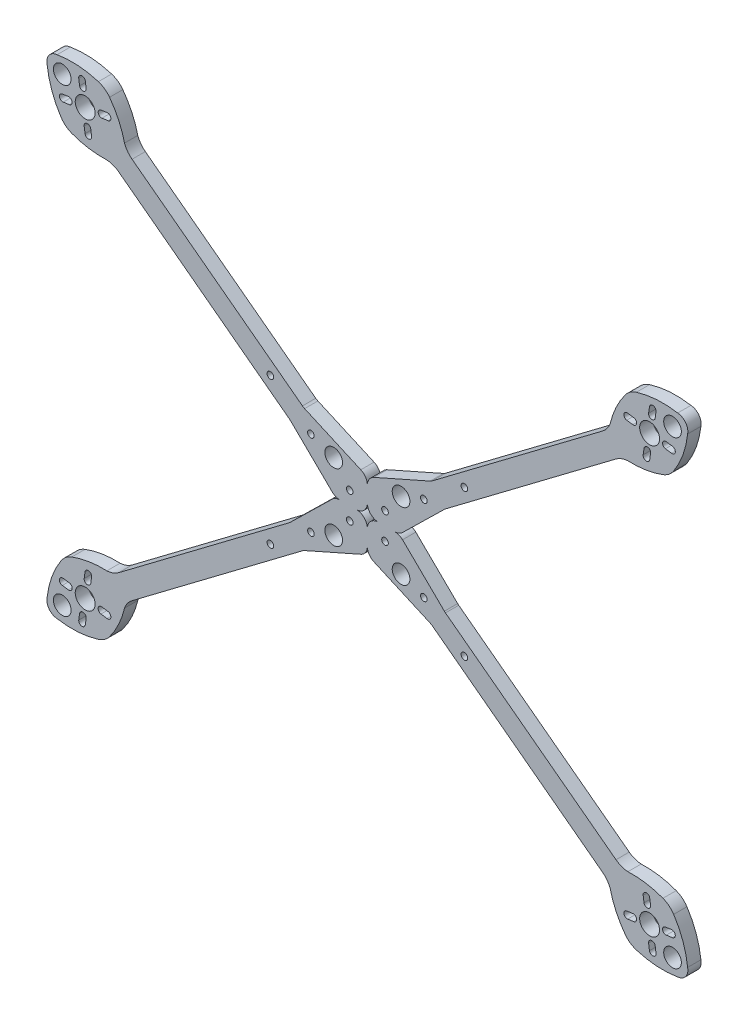
SolidWorks part; units mm, degrees
ref_plane "Alzado" through (0, 0, 0) normal (0, 0, 1) x (1, 0, 0)
ref_plane "Planta" through (0, 0, 0) normal (0, 1, 0) x (1, 0, 0)
ref_plane "Vista lateral" through (0, 0, 0) normal (1, 0, 0) x (0, 0, -1)
sketch "Croquis1" plane through (0, 0, 0) normal (0, 0, 1) x (1, 0, 0)
  line L0 (-166.1256, 84.824) -> (-181.6394, 96.5144) construction
  line L1 (-181.6394, 96.5144) -> (-187.6575, 88.5281) construction
  line L2 (-187.6575, 88.5281) -> (-171.8329, 76.6034) construction
  line L3 (-136.7303, 61.4124) -> (-136.7303, 68.4084)
  line L4 (-139.7056, 72.9801) -> (-165.1413, 84.2454)
  line L5 (-136.7303, 56.4124) -> (-264.512, 152.7028) construction
  line L6 (-141.7303, 56.4124) -> (-149.1592, 56.4124)
  line L7 (-152.6561, 57.8386) -> (-171.6025, 76.3779)
  line L8 (-264.512, 152.7028) -> (-274.8943, 160.5264) construction
  line L9 (-264.512, 152.7028) -> (-266.1473, 164.3384) construction
  line L11 (-267.4239, 162.6443) -> (-267.0343, 159.8715)
  line L15 (-264.0635, 160.289) -> (-264.4531, 163.0618)
  line L19 (-267.6327, 164.1297) -> (-267.4239, 162.6443) construction
  line L20 (-267.4239, 162.6443) -> (-264.4531, 163.0618) construction
  line L21 (-266.8255, 158.3861) -> (-267.0343, 159.8715) construction
  line L22 (-267.0343, 159.8715) -> (-264.0635, 160.289) construction
  line L23 (-254.5705, 155.6147) -> (-257.3433, 155.225)
  line L24 (-256.9258, 152.2542) -> (-254.153, 152.6439)
  line L25 (-261.6001, 142.7613) -> (-261.9898, 145.534)
  line L26 (-264.9606, 145.1165) -> (-264.5709, 142.3438)
  line L27 (-274.4535, 149.7908) -> (-271.6808, 150.1805)
  line L28 (-272.0983, 153.1513) -> (-274.871, 152.7616)
  line L29 (-172.0904, 76.7974) -> (-249.3006, 134.9795)
  line L30 (-264.512, 152.7028) -> (-273.5392, 140.7232) construction
  line L31 (-263.0855, 142.5525) -> (-262.8767, 141.0671) construction
  line L32 (-274.8943, 160.5264) -> (-282.8806, 166.5445) construction
  line L33 (-262.8767, 141.0671) -> (-262.3693, 137.4568) construction
  line L34 (-274.6623, 151.2762) -> (-276.1477, 151.0675) construction
  line L35 (-276.1477, 151.0675) -> (-279.6136, 150.5804) construction
  line L36 (-165.8148, 84.5898) -> (-243.2825, 142.9659)
  line L37 (-276.1477, -38.2428) -> (-279.6136, -37.7557) construction
  line L38 (-274.6623, -38.4515) -> (-276.1477, -38.2428) construction
  line L39 (-262.8767, -28.2424) -> (-262.3693, -24.6321) construction
  line L40 (-274.8943, -47.7016) -> (-282.8806, -53.7198) construction
  line L41 (-263.0855, -29.7278) -> (-262.8767, -28.2424) construction
  line L42 (-264.512, -39.878) -> (-273.5392, -27.8985) construction
  line L43 (-267.0343, -47.0468) -> (-264.0635, -47.4643) construction
  line L44 (-266.8255, -45.5614) -> (-267.0343, -47.0468) construction
  line L45 (-267.4239, -49.8195) -> (-264.4531, -50.237) construction
  line L46 (-267.6327, -51.3049) -> (-267.4239, -49.8195) construction
  line L47 (-264.512, -39.878) -> (-266.1473, -51.5137) construction
  line L48 (-264.512, -39.878) -> (-274.8943, -47.7016) construction
  line L49 (-136.7303, 56.4124) -> (-264.512, -39.878) construction
  line L50 (-187.6575, 24.2966) -> (-171.8329, 36.2213) construction
  line L51 (-181.6394, 16.3103) -> (-187.6575, 24.2966) construction
  line L52 (-166.1256, 28.0008) -> (-181.6394, 16.3103) construction
  line L53 (-165.8148, 28.235) -> (-243.2825, -30.1411)
  line L54 (-172.0904, 36.0273) -> (-249.3006, -22.1548)
  line L55 (-272.0983, -40.3266) -> (-274.871, -39.9369)
  line L56 (-274.4535, -36.9661) -> (-271.6808, -37.3558)
  line L57 (-264.9606, -32.2918) -> (-264.5709, -29.519)
  line L58 (-261.6001, -29.9366) -> (-261.9898, -32.7093)
  line L59 (-256.9258, -39.4295) -> (-254.153, -39.8192)
  line L60 (-254.5705, -42.79) -> (-257.3433, -42.4003)
  line L61 (-264.0635, -47.4643) -> (-264.4531, -50.237)
  line L62 (-267.4239, -49.8195) -> (-267.0343, -47.0468)
  line L63 (-152.6561, 54.9861) -> (-171.6025, 36.4468)
  line L64 (-139.7056, 39.8447) -> (-165.1413, 28.5793)
  line L65 (-136.7303, 51.4124) -> (-136.7303, 44.4163)
  line L66 (-107.3351, 28.0008) -> (-91.8213, 16.3103) construction
  line L67 (-91.8213, 16.3103) -> (-85.8031, 24.2966) construction
  line L68 (-85.8031, 24.2966) -> (-101.6277, 36.2213) construction
  line L69 (-136.7303, 56.4124) -> (-8.9487, -39.878) construction
  line L70 (-8.9487, -39.878) -> (1.4336, -47.7016) construction
  line L71 (-8.9487, -39.878) -> (-7.3134, -51.5137) construction
  line L72 (-5.828, -51.3049) -> (-6.0367, -49.8195) construction
  line L73 (-6.0367, -49.8195) -> (-9.0075, -50.237) construction
  line L74 (-6.6352, -45.5614) -> (-6.4264, -47.0468) construction
  line L75 (-6.4264, -47.0468) -> (-9.3972, -47.4643) construction
  line L76 (-8.9487, -39.878) -> (0.0786, -27.8985) construction
  line L77 (-10.3752, -29.7278) -> (-10.5839, -28.2424) construction
  line L78 (1.4336, -47.7016) -> (9.42, -53.7198) construction
  line L79 (-10.5839, -28.2424) -> (-11.0913, -24.6321) construction
  line L80 (1.2016, -38.4515) -> (2.687, -38.2428) construction
  line L81 (2.687, -38.2428) -> (6.1529, -37.7557) construction
  line L82 (2.687, 151.0675) -> (6.1529, 150.5804) construction
  line L83 (1.2016, 151.2762) -> (2.687, 151.0675) construction
  line L84 (-10.5839, 141.0671) -> (-11.0913, 137.4568) construction
  line L85 (1.4336, 160.5264) -> (9.42, 166.5445) construction
  line L86 (-10.3752, 142.5525) -> (-10.5839, 141.0671) construction
  line L87 (-8.9487, 152.7028) -> (0.0786, 140.7232) construction
  line L88 (-6.4264, 159.8715) -> (-9.3972, 160.289) construction
  line L89 (-6.6352, 158.3861) -> (-6.4264, 159.8715) construction
  line L90 (-6.0367, 162.6443) -> (-9.0075, 163.0618) construction
  line L91 (-5.828, 164.1297) -> (-6.0367, 162.6443) construction
  line L92 (-8.9487, 152.7028) -> (-7.3134, 164.3384) construction
  line L93 (-8.9487, 152.7028) -> (1.4336, 160.5264) construction
  line L94 (-136.7303, 56.4124) -> (-8.9487, 152.7028) construction
  line L95 (-85.8031, 88.5281) -> (-101.6277, 76.6034) construction
  line L96 (-91.8213, 96.5144) -> (-85.8031, 88.5281) construction
  line L97 (-107.3351, 84.824) -> (-91.8213, 96.5144) construction
  line L98 (-133.7551, 39.8447) -> (-108.3194, 28.5793)
  line L99 (-120.8046, 54.9861) -> (-101.8581, 36.4468)
  line L100 (-6.0367, -49.8195) -> (-6.4264, -47.0468)
  line L101 (-9.3972, -47.4643) -> (-9.0075, -50.237)
  line L102 (-18.8901, -42.79) -> (-16.1174, -42.4003)
  line L103 (-16.5349, -39.4295) -> (-19.3077, -39.8192)
  line L104 (-11.8606, -29.9366) -> (-11.4709, -32.7093)
  line L105 (-8.5001, -32.2918) -> (-8.8898, -29.519)
  line L106 (0.9928, -36.9661) -> (-1.7799, -37.3558)
  line L107 (-1.3624, -40.3266) -> (1.4103, -39.9369)
  line L108 (-101.3703, 36.0273) -> (-24.16, -22.1548)
  line L109 (-107.6459, 28.235) -> (-30.1782, -30.1411)
  line L110 (-107.6459, 84.5898) -> (-30.1782, 142.9659)
  line L111 (-101.3703, 76.7974) -> (-24.16, 134.9795)
  line L112 (-1.3624, 153.1513) -> (1.4103, 152.7616)
  line L113 (0.9928, 149.7908) -> (-1.7799, 150.1805)
  line L114 (-8.5001, 145.1165) -> (-8.8898, 142.3438)
  line L115 (-11.8606, 142.7613) -> (-11.4709, 145.534)
  line L116 (-16.5349, 152.2542) -> (-19.3077, 152.6439)
  line L117 (-18.8901, 155.6147) -> (-16.1174, 155.225)
  line L118 (-9.3972, 160.289) -> (-9.0075, 163.0618)
  line L119 (-6.0367, 162.6443) -> (-6.4264, 159.8715)
  line L120 (-120.8046, 57.8386) -> (-101.8581, 76.3779)
  line L121 (-131.7303, 56.4124) -> (-124.3015, 56.4124)
  line L122 (-133.7551, 72.9801) -> (-108.3194, 84.2454)
  circle A0 centre (-180.6553, 89.5122) radius 1.5
  circle A1 centre (-162.2906, 75.6734) radius 1.5
  circle A2 centre (-151.9803, 71.6624) radius 4
  circle A3 centre (-144.7167, 62.4305) radius 1.5
  circle A5 centre (-136.7303, 56.4124) radius 10 construction
  circle A6 centre (-136.7303, 56.4124) radius 160 construction
  circle A7 centre (-264.512, 152.7028) radius 4.5
  circle A8 centre (-274.8943, 160.5264) radius 4
  arc A9 (-267.4239, 162.6443) -> (-264.4531, 163.0618) centre (-265.9385, 162.853) cw
  arc A10 (-267.0343, 159.8715) -> (-264.0635, 160.289) centre (-265.5489, 160.0803) ccw
  arc A11 (-254.5705, 155.6147) -> (-254.153, 152.6439) centre (-254.3618, 154.1293) cw
  arc A12 (-257.3433, 155.225) -> (-256.9258, 152.2542) centre (-257.1345, 153.7396) ccw
  arc A13 (-261.6001, 142.7613) -> (-264.5709, 142.3438) centre (-263.0855, 142.5525) cw
  arc A14 (-261.9898, 145.534) -> (-264.9606, 145.1165) centre (-263.4752, 145.3253) ccw
  arc A15 (-274.4535, 149.7908) -> (-274.871, 152.7616) centre (-274.6623, 151.2762) cw
  arc A16 (-271.6808, 150.1805) -> (-272.0983, 153.1513) centre (-271.8895, 151.6659) ccw
  arc A17 (-249.3006, 134.9795) -> (-254.6905, 136.9734) centre (-255.3188, 126.9931) ccw
  arc A18 (-254.6905, 136.9734) -> (-270.5641, 139.4702) centre (-256.5386, 176.9307) cw
  arc A19 (-277.233, 166.9825) -> (-281.7449, 160.995) centre (-276.8465, 161.9974) ccw
  arc A20 (-281.7449, 160.995) -> (-275.418, 143.3485) centre (-241.9768, 165.2959) ccw
  arc A21 (-270.5641, 139.4702) -> (-275.418, 143.3485) centre (-267.0577, 148.8353) cw
  arc A22 (-243.2825, 142.9659) -> (-246.6848, 147.5973) centre (-237.2643, 150.9522) cw
  arc A23 (-246.6848, 147.5973) -> (-253.4602, 162.1678) centre (-285.6036, 138.3601) ccw
  arc A24 (-253.4602, 162.1678) -> (-258.5262, 165.7647) centre (-261.4961, 156.2159) ccw
  arc A25 (-277.233, 166.9825) -> (-258.5262, 165.7647) centre (-270.4057, 127.5694) cw
  arc A26 (-149.1592, 56.4124) -> (-152.6561, 57.8386) centre (-149.1592, 61.4124) cw
  arc A27 (-136.7303, 61.4124) -> (-141.7303, 56.4124) centre (-141.7303, 61.4124) cw
  arc A28 (-136.7303, 68.4084) -> (-139.7056, 72.9801) centre (-141.7303, 68.4084) ccw
  arc A29 (-166.1256, 84.824) -> (-165.1413, 84.2454) centre (-163.1165, 88.8171) ccw
  arc A30 (-171.6025, 76.3779) -> (-172.0904, 76.7974) centre (-175.0995, 72.8042) ccw
  arc A31 (-171.6025, 36.4468) -> (-172.0904, 36.0273) centre (-175.0995, 40.0205) cw
  arc A32 (-166.1256, 28.0008) -> (-165.1413, 28.5793) centre (-163.1165, 24.0076) cw
  arc A33 (-136.7303, 44.4163) -> (-139.7056, 39.8447) centre (-141.7303, 44.4163) cw
  arc A34 (-136.7303, 51.4124) -> (-141.7303, 56.4124) centre (-141.7303, 51.4124) ccw
  arc A35 (-149.1592, 56.4124) -> (-152.6561, 54.9861) centre (-149.1592, 51.4124) ccw
  arc A36 (-277.233, -54.1577) -> (-258.5262, -52.9399) centre (-270.4057, -14.7447) ccw
  arc A37 (-253.4602, -49.343) -> (-258.5262, -52.9399) centre (-261.4961, -43.3911) cw
  arc A38 (-246.6848, -34.7726) -> (-253.4602, -49.343) centre (-285.6036, -25.5354) cw
  arc A39 (-243.2825, -30.1411) -> (-246.6848, -34.7726) centre (-237.2643, -38.1275) ccw
  arc A40 (-270.5641, -26.6455) -> (-275.418, -30.5238) centre (-267.0577, -36.0106) ccw
  arc A41 (-281.7449, -48.1702) -> (-275.418, -30.5238) centre (-241.9768, -52.4711) cw
  arc A42 (-277.233, -54.1577) -> (-281.7449, -48.1702) centre (-276.8465, -49.1727) cw
  arc A43 (-254.6905, -24.1487) -> (-270.5641, -26.6455) centre (-256.5386, -64.1059) ccw
  arc A44 (-249.3006, -22.1548) -> (-254.6905, -24.1487) centre (-255.3188, -14.1684) cw
  arc A45 (-271.6808, -37.3558) -> (-272.0983, -40.3266) centre (-271.8895, -38.8412) cw
  arc A46 (-274.4535, -36.9661) -> (-274.871, -39.9369) centre (-274.6623, -38.4515) ccw
  arc A47 (-261.9898, -32.7093) -> (-264.9606, -32.2918) centre (-263.4752, -32.5005) cw
  arc A48 (-261.6001, -29.9366) -> (-264.5709, -29.519) centre (-263.0855, -29.7278) ccw
  arc A49 (-257.3433, -42.4003) -> (-256.9258, -39.4295) centre (-257.1345, -40.9149) cw
  arc A50 (-254.5705, -42.79) -> (-254.153, -39.8192) centre (-254.3618, -41.3046) ccw
  arc A51 (-267.0343, -47.0468) -> (-264.0635, -47.4643) centre (-265.5489, -47.2555) cw
  arc A52 (-267.4239, -49.8195) -> (-264.4531, -50.237) centre (-265.9385, -50.0283) ccw
  circle A53 centre (-274.8943, -47.7016) radius 4
  circle A54 centre (-264.512, -39.878) radius 4.5
  circle A55 centre (-144.7167, 50.3942) radius 1.5
  circle A56 centre (-151.9803, 41.1624) radius 4
  circle A57 centre (-162.2906, 37.1513) radius 1.5
  circle A58 centre (-180.6553, 23.3125) radius 1.5
  circle A59 centre (-92.8054, 23.3125) radius 1.5
  circle A60 centre (-111.1701, 37.1513) radius 1.5
  circle A61 centre (-121.4803, 41.1624) radius 4
  circle A62 centre (-128.744, 50.3942) radius 1.5
  circle A63 centre (-8.9487, -39.878) radius 4.5
  circle A64 centre (1.4336, -47.7016) radius 4
  arc A65 (-6.0367, -49.8195) -> (-9.0075, -50.237) centre (-7.5221, -50.0283) cw
  arc A66 (-6.4264, -47.0468) -> (-9.3972, -47.4643) centre (-7.9118, -47.2555) ccw
  arc A67 (-18.8901, -42.79) -> (-19.3077, -39.8192) centre (-19.0989, -41.3046) cw
  arc A68 (-16.1174, -42.4003) -> (-16.5349, -39.4295) centre (-16.3262, -40.9149) ccw
  arc A69 (-11.8606, -29.9366) -> (-8.8898, -29.519) centre (-10.3752, -29.7278) cw
  arc A70 (-11.4709, -32.7093) -> (-8.5001, -32.2918) centre (-9.9855, -32.5005) ccw
  arc A71 (0.9928, -36.9661) -> (1.4103, -39.9369) centre (1.2016, -38.4515) cw
  arc A72 (-1.7799, -37.3558) -> (-1.3624, -40.3266) centre (-1.5712, -38.8412) ccw
  arc A73 (-24.16, -22.1548) -> (-18.7702, -24.1487) centre (-18.1419, -14.1684) ccw
  arc A74 (-18.7702, -24.1487) -> (-2.8966, -26.6455) centre (-16.9221, -64.1059) cw
  arc A75 (3.7724, -54.1577) -> (8.2843, -48.1702) centre (3.3858, -49.1727) ccw
  arc A76 (8.2843, -48.1702) -> (1.9573, -30.5238) centre (-31.4839, -52.4711) ccw
  arc A77 (-2.8966, -26.6455) -> (1.9573, -30.5238) centre (-6.403, -36.0106) cw
  arc A78 (-30.1782, -30.1411) -> (-26.7759, -34.7726) centre (-36.1963, -38.1275) cw
  arc A79 (-26.7759, -34.7726) -> (-20.0004, -49.343) centre (12.1429, -25.5354) ccw
  arc A80 (-20.0004, -49.343) -> (-14.9345, -52.9399) centre (-11.9646, -43.3911) ccw
  arc A81 (3.7724, -54.1577) -> (-14.9345, -52.9399) centre (-3.0549, -14.7447) cw
  arc A82 (-124.3015, 56.4124) -> (-120.8046, 54.9861) centre (-124.3015, 51.4124) cw
  arc A83 (-136.7303, 51.4124) -> (-131.7303, 56.4124) centre (-131.7303, 51.4124) cw
  arc A84 (-136.7303, 44.4163) -> (-133.7551, 39.8447) centre (-131.7303, 44.4163) ccw
  arc A85 (-107.3351, 28.0008) -> (-108.3194, 28.5793) centre (-110.3442, 24.0076) ccw
  arc A86 (-101.8581, 36.4468) -> (-101.3703, 36.0273) centre (-98.3612, 40.0205) ccw
  arc A87 (-101.8581, 76.3779) -> (-101.3703, 76.7974) centre (-98.3612, 72.8042) cw
  arc A88 (-107.3351, 84.824) -> (-108.3194, 84.2454) centre (-110.3442, 88.8171) cw
  arc A89 (-136.7303, 68.4084) -> (-133.7551, 72.9801) centre (-131.7303, 68.4084) cw
  arc A90 (-136.7303, 61.4124) -> (-131.7303, 56.4124) centre (-131.7303, 61.4124) ccw
  arc A91 (-124.3015, 56.4124) -> (-120.8046, 57.8386) centre (-124.3015, 61.4124) ccw
  arc A92 (3.7724, 166.9825) -> (-14.9345, 165.7647) centre (-3.0549, 127.5694) ccw
  arc A93 (-20.0004, 162.1678) -> (-14.9345, 165.7647) centre (-11.9646, 156.2159) cw
  arc A94 (-26.7759, 147.5973) -> (-20.0004, 162.1678) centre (12.1429, 138.3601) cw
  arc A95 (-30.1782, 142.9659) -> (-26.7759, 147.5973) centre (-36.1963, 150.9522) ccw
  arc A96 (-2.8966, 139.4702) -> (1.9573, 143.3485) centre (-6.403, 148.8353) ccw
  arc A97 (8.2843, 160.995) -> (1.9573, 143.3485) centre (-31.4839, 165.2959) cw
  arc A98 (3.7724, 166.9825) -> (8.2843, 160.995) centre (3.3858, 161.9974) cw
  arc A99 (-18.7702, 136.9734) -> (-2.8966, 139.4702) centre (-16.9221, 176.9307) ccw
  arc A100 (-24.16, 134.9795) -> (-18.7702, 136.9734) centre (-18.1419, 126.9931) cw
  arc A101 (-1.7799, 150.1805) -> (-1.3624, 153.1513) centre (-1.5712, 151.6659) cw
  arc A102 (0.9928, 149.7908) -> (1.4103, 152.7616) centre (1.2016, 151.2762) ccw
  arc A103 (-11.4709, 145.534) -> (-8.5001, 145.1165) centre (-9.9855, 145.3253) cw
  arc A104 (-11.8606, 142.7613) -> (-8.8898, 142.3438) centre (-10.3752, 142.5525) ccw
  arc A105 (-16.1174, 155.225) -> (-16.5349, 152.2542) centre (-16.3262, 153.7396) cw
  arc A106 (-18.8901, 155.6147) -> (-19.3077, 152.6439) centre (-19.0989, 154.1293) ccw
  arc A107 (-6.4264, 159.8715) -> (-9.3972, 160.289) centre (-7.9118, 160.0803) cw
  arc A108 (-6.0367, 162.6443) -> (-9.0075, 163.0618) centre (-7.5221, 162.853) ccw
  circle A109 centre (1.4336, 160.5264) radius 4
  circle A110 centre (-8.9487, 152.7028) radius 4.5
  circle A111 centre (-128.744, 62.4305) radius 1.5
  circle A112 centre (-121.4803, 71.6624) radius 4
  circle A113 centre (-111.1701, 75.6734) radius 1.5
  circle A114 centre (-92.8054, 89.5122) radius 1.5
  point P52 (-264.512, 152.7028)
  point P60 (-251.6965, 136.7849)
  point P80 (-151.1985, 56.4124)
  point P86 (-136.7303, 71.6624)
  point P171 (-136.7303, 41.1624)
  point P172 (-251.6965, -23.9602)
  point P333 (-21.7642, -23.9602)
  point P334 (-122.2622, 56.4124)
  point P335 (-21.7642, 136.7849)
  dimension "D1" = 45
  dimension "D17" = 8
  dimension "D18" = 9
  dimension "D21" = 10
  dimension "D23" = 40
  dimension "D24" = 5
  dimension "D25" = 10
  dimension "D26" = 5
  dimension "D2" = 11.75
  dimension "D3" = 3
  dimension "D4" = 4
  dimension "D5" = 1.5
  dimension "D6" = 10
  dimension "D7" = 32.0049
  dimension "D8" = 21.5668
  dimension "D9" = 3.0015
  dimension "D12" = 22.9951
  dimension "D13" = 14.4682
  dimension "D14" = 15.25
  dimension "D15" = 100
  dimension "D16" = 13
  dimension "D19" = 10
  dimension "D20" = 15
  dimension "D22" = 5
extrude "Saliente-Extruir1" add sketch "Croquis1" along normal blind 6
sketch "Croquis3" plane through (0, 0, 6) normal (0, 0, 1) x (1, 0, 0)
  line L0 (-180.6553, 89.5122) -> (-184.6485, 92.5213) construction
  line L1 (-184.6485, 92.5213) -> (-183.4419, 94.1225)
  line L2 (-166.1256, 84.824) -> (-243.2825, 142.9659) construction
  line L3 (-179.2445, 94.7159) -> (-167.4653, 85.8698)
  line L4 (-163.5753, 83.5848) -> (-139.7056, 72.9801)
  line L5 (-184.6485, 92.5213) -> (-185.8558, 90.9191)
  line L6 (-172.0904, 76.7974) -> (-249.3006, 134.9795) construction
  line L7 (-185.2703, 86.7214) -> (-172.6143, 77.1436)
  line L8 (-170.6957, 75.4906) -> (-162.1293, 67.1083)
  line L9 (-152.6561, 57.8386) -> (-171.6025, 76.3779) construction
  line L10 (-136.7303, 68.4084) -> (-136.7303, 61.4124) construction
  line L11 (-136.7303, 61.4124) -> (-141.7303, 56.4124) construction
  line L12 (-141.7303, 56.4124) -> (-149.1592, 56.4124) construction
  line L13 (-170.6957, 37.3342) -> (-162.1293, 45.7164)
  line L14 (-185.2703, 26.1033) -> (-172.6143, 35.6811)
  line L15 (-184.6485, 20.3035) -> (-185.8558, 21.9057)
  line L16 (-163.5753, 29.2399) -> (-139.7056, 39.8447)
  line L17 (-179.2445, 18.1089) -> (-167.4653, 26.9549)
  line L18 (-184.6485, 20.3035) -> (-183.4419, 18.7023)
  line L19 (-88.8122, 20.3035) -> (-90.0188, 18.7023)
  line L20 (-94.2162, 18.1089) -> (-105.9954, 26.9549)
  line L21 (-109.8854, 29.2399) -> (-133.7551, 39.8447)
  line L22 (-88.8122, 20.3035) -> (-87.6049, 21.9057)
  line L23 (-88.1904, 26.1033) -> (-100.8464, 35.6811)
  line L24 (-102.765, 37.3342) -> (-111.3314, 45.7164)
  line L25 (-102.765, 75.4906) -> (-111.3314, 67.1083)
  line L26 (-88.1904, 86.7214) -> (-100.8464, 77.1436)
  line L27 (-88.8122, 92.5213) -> (-87.6049, 90.9191)
  line L28 (-109.8854, 83.5848) -> (-133.7551, 72.9801)
  line L29 (-94.2162, 94.7159) -> (-105.9954, 85.8698)
  line L30 (-88.8122, 92.5213) -> (-90.0188, 94.1225)
  arc A0 (-166.1256, 84.824) -> (-165.1413, 84.2454) centre (-163.1165, 88.8171) ccw construction
  arc A1 (-185.8558, 90.9191) -> (-185.2703, 86.7214) centre (-183.4599, 89.1136) ccw
  arc A2 (-183.4419, 94.1225) -> (-179.2445, 94.7159) centre (-181.046, 92.317) cw
  arc A3 (-183.4419, 18.7023) -> (-179.2445, 18.1089) centre (-181.046, 20.5077) ccw
  arc A4 (-185.8558, 21.9057) -> (-185.2703, 26.1033) centre (-183.4599, 23.7111) cw
  arc A5 (-87.6049, 21.9057) -> (-88.1904, 26.1033) centre (-90.0008, 23.7111) ccw
  arc A6 (-90.0188, 18.7023) -> (-94.2162, 18.1089) centre (-92.4147, 20.5077) cw
  arc A7 (-90.0188, 94.1225) -> (-94.2162, 94.7159) centre (-92.4147, 92.317) ccw
  arc A8 (-87.6049, 90.9191) -> (-88.1904, 86.7214) centre (-90.0008, 89.1136) cw
  arc A9 (-162.1293, 67.1083) -> (-162.1293, 45.7164) centre (-172.8253, 56.4124) cw
  arc A10 (-111.3314, 45.7164) -> (-111.3314, 67.1083) centre (-100.6354, 56.4124) cw
  arc A11 (-139.7056, 72.9801) -> (-133.7551, 72.9801) centre (-136.7303, 82.5272) ccw
  arc A12 (-139.7056, 39.8447) -> (-133.7551, 39.8447) centre (-136.7303, 30.2975) cw
  arc A13 (-167.4653, 85.8698) -> (-163.5753, 83.5848) centre (-155.4552, 101.8622) ccw
  arc A14 (-172.6143, 77.1436) -> (-170.6957, 75.4906) centre (-184.6834, 61.1957) cw
  arc A15 (-170.6957, 37.3342) -> (-172.6143, 35.6811) centre (-184.6834, 51.6291) cw
  arc A16 (-163.5753, 29.2399) -> (-167.4653, 26.9549) centre (-155.4552, 10.9626) ccw
  arc A17 (-105.9954, 26.9549) -> (-109.8854, 29.2399) centre (-118.0055, 10.9626) ccw
  arc A18 (-100.8464, 35.6811) -> (-102.765, 37.3342) centre (-88.7773, 51.6291) cw
  arc A19 (-102.765, 75.4906) -> (-100.8464, 77.1436) centre (-88.7773, 61.1957) cw
  arc A20 (-109.8854, 83.5848) -> (-105.9954, 85.8698) centre (-118.0055, 101.8622) ccw
  circle A21 centre (-180.6553, 89.5122) radius 1.5
  circle A22 centre (-162.2906, 75.6734) radius 1.5
  circle A23 centre (-144.7167, 62.4305) radius 1.5
  circle A24 centre (-151.9803, 71.6624) radius 1.5
  circle A25 centre (-128.744, 62.4305) radius 1.5
  circle A26 centre (-121.4803, 71.6624) radius 1.5
  circle A27 centre (-111.1701, 75.6734) radius 1.5
  circle A28 centre (-92.8054, 89.5122) radius 1.5
  circle A29 centre (-92.8054, 23.3125) radius 1.5
  circle A30 centre (-111.1701, 37.1513) radius 1.5
  circle A31 centre (-121.4803, 41.1624) radius 1.5
  circle A32 centre (-128.744, 50.3942) radius 1.5
  circle A33 centre (-144.7167, 50.3942) radius 1.5
  circle A34 centre (-151.9803, 41.1624) radius 1.5
  circle A35 centre (-162.2906, 37.1513) radius 1.5
  circle A36 centre (-180.6553, 23.3125) radius 1.5
  point P24 (-187.6575, 88.5281)
  point P27 (-181.6394, 96.5144)
  point P45 (-181.6394, 16.3103)
  point P46 (-187.6575, 24.2966)
  point P59 (-85.8031, 24.2966)
  point P60 (-91.8213, 16.3103)
  point P77 (-165.65, 84.5065)
  point P80 (-171.6025, 76.3779)
  point P83 (-171.6025, 36.4468)
  point P86 (-165.65, 28.3182)
  point P89 (-107.8107, 28.3182)
  point P92 (-101.8581, 36.4468)
  point P95 (-101.8581, 76.3779)
  point P98 (-107.8107, 84.5065)
  dimension "D2" = 3
  dimension "D3" = 20
  dimension "D1" = 5
